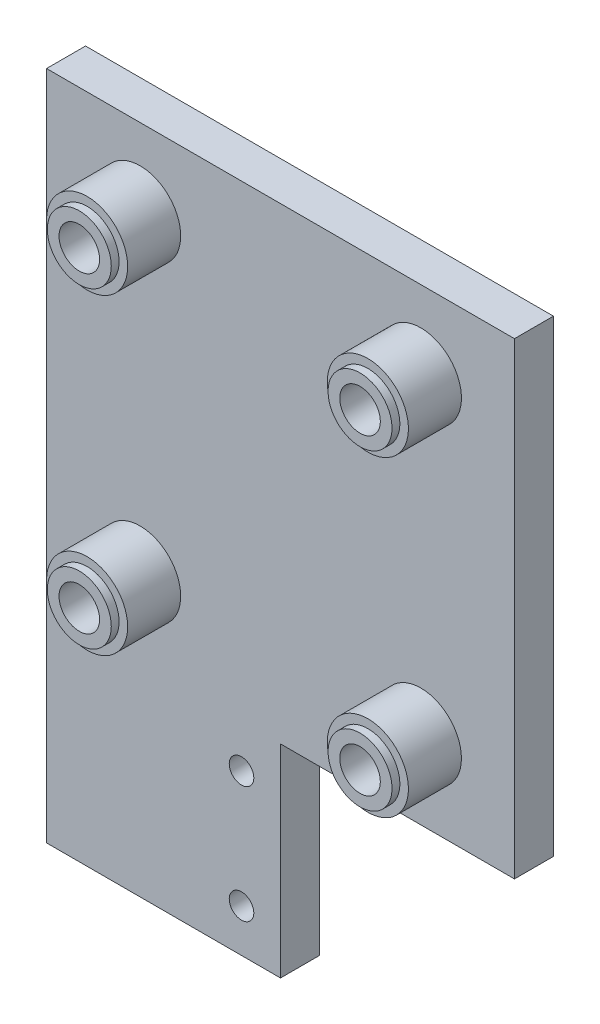
SolidWorks part; units mm, degrees
ref_plane "Front Plane" through (0, 0, 0) normal (0, 0, 1) x (1, 0, 0)
ref_plane "Top Plane" through (0, 0, 0) normal (0, 1, 0) x (1, 0, 0)
ref_plane "Right Plane" through (0, 0, 0) normal (1, 0, 0) x (0, 0, -1)
sketch "Sketch1" plane through (0, 0, 0) normal (0, 0, 1) x (1, 0, 0)
  line L1 (-19.05, -38.1) -> (19.05, -38.1)
  line L2 (-19.05, -38.1) -> (-19.05, 38.1)
  line L3 (-19.05, 38.1) -> (19.05, 38.1)
  line L4 (19.05, -38.1) -> (19.05, 38.1)
  line L5 (-19.05, -38.1) -> (19.05, 38.1) construction
  line L6 (-19.05, 38.1) -> (19.05, -38.1) construction
  point P0 (0, 0)
  dimension "D1" = 38.1
  dimension "D2" = 76.2
extrude "Boss-Extrude1" add sketch "Sketch1" along normal blind 6.35
sketch "Sketch8" plane through (0, 0, 6.35) normal (0, 0, 1) x (1, 0, 0)
  line L0 (19.05, 38.1) -> (-19.05, 38.1) construction
  line L1 (-19.05, 38.1) -> (-38.1, 38.1)
  line L2 (-19.05, 38.1) -> (-19.05, -38.1)
  line L3 (-19.05, -38.1) -> (-38.1, -38.1)
  line L4 (-38.1, 38.1) -> (-38.1, -38.1)
  line L5 (-19.05, 38.1) -> (-19.05, -38.1) construction
  line L6 (-19.05, -38.1) -> (19.05, -38.1) construction
  line L7 (0, 38.1) -> (0, -38.1) construction
  line L8 (19.05, -38.1) -> (38.1, -38.1)
  line L9 (38.1, 38.1) -> (38.1, -38.1)
  line L10 (19.05, 38.1) -> (38.1, 38.1)
  line L11 (19.05, 38.1) -> (19.05, -38.1)
  dimension "D1" = 38.1
extrude "Boss-Extrude5" add sketch "Sketch8" against normal up to surface (6.35 mm away) up to face at (0, 0, 0)
sketch "Sketch5" plane through (0, 0, 6.35) normal (0, 0, 1) x (1, 0, 0)
  line L0 (38.1, 38.1) -> (-38.1, 38.1) construction
  line L1 (0, 38.1) -> (0, -38.1) construction
  line L2 (38.1, 38.1) -> (-38.1, 38.1) construction
  line L3 (-38.1, -38.1) -> (38.1, -38.1) construction
  circle A0 centre (22.86, 25.4) radius 6.604
  circle A1 centre (-22.86, 25.4) radius 6.604
  dimension "D1" = 13.208
  dimension "D2" = 12.7
  dimension "D3" = 22.86
extrude "Boss-Extrude2" add sketch "Sketch5" along normal blind 9.906
sketch "Sketch6" plane through (0, 0, 16.256) normal (0, 0, 1) x (1, 0, 0)
  line L0 (0, 38.1) -> (0, -38.1) construction
  line L1 (38.1, 38.1) -> (-38.1, 38.1) construction
  line L2 (-38.1, -38.1) -> (38.1, -38.1) construction
  circle A0 centre (22.86, 25.4) radius 3.302
  circle A1 centre (-22.86, 25.4) radius 3.302
  dimension "D1" = 6.604
extrude "Cut-Extrude3" cut sketch "Sketch6" against normal through all
sketch "Sketch9" plane through (0, 0, 16.256) normal (0, 0, 1) x (1, 0, 0)
  line L0 (0, 38.1) -> (0, -38.1) construction
  line L1 (38.1, 38.1) -> (-38.1, 38.1) construction
  line L2 (-38.1, -38.1) -> (38.1, -38.1) construction
  circle A0 centre (-22.86, 25.4) radius 5.207
  circle A1 centre (-22.86, 25.4) radius 6.604
  circle A2 centre (-22.86, 25.4) radius 3.302 construction
  circle A3 centre (-22.86, 25.4) radius 6.604 construction
  circle A4 centre (22.86, 25.4) radius 6.604
  circle A5 centre (22.86, 25.4) radius 5.207
  dimension "D1" = 10.414
extrude "Cut-Extrude4" cut sketch "Sketch9" against normal blind 1.27
mirror "Mirror1" about plane through (0, 0, 0) normal (0, 1, 0) of "Cut-Extrude3", "Boss-Extrude2", "Cut-Extrude4"
sketch "Sketch11" plane through (0, 0, 0) normal (0, 0, -1) x (-1, 0, 0)
  line L0 (38.1, -38.1) -> (-38.1, -38.1) construction
  line L1 (0, -38.1) -> (38.1, -38.1)
  line L2 (0, -38.1) -> (0, -71.12)
  line L3 (0, -71.12) -> (38.1, -71.12)
  line L4 (38.1, -38.1) -> (38.1, -71.12)
  line L5 (38.1, 38.1) -> (38.1, -38.1) construction
  line L6 (0, -54.61) -> (38.1, -54.61) construction
  circle A0 centre (6.35, -64.135) radius 2
  circle A1 centre (6.35, -45.085) radius 2
  point P12 (6.7691, -44.45)
  point P13 (6.7878, -65.9582)
  dimension "D2" = 4
  dimension "D1" = 33.02
  dimension "D3" = 6.35
  dimension "D4" = 9.525
extrude "Boss-Extrude6" add sketch "Sketch11" against normal up to surface (6.35 mm away) up to face at (29.464, -25.4, 6.35)
